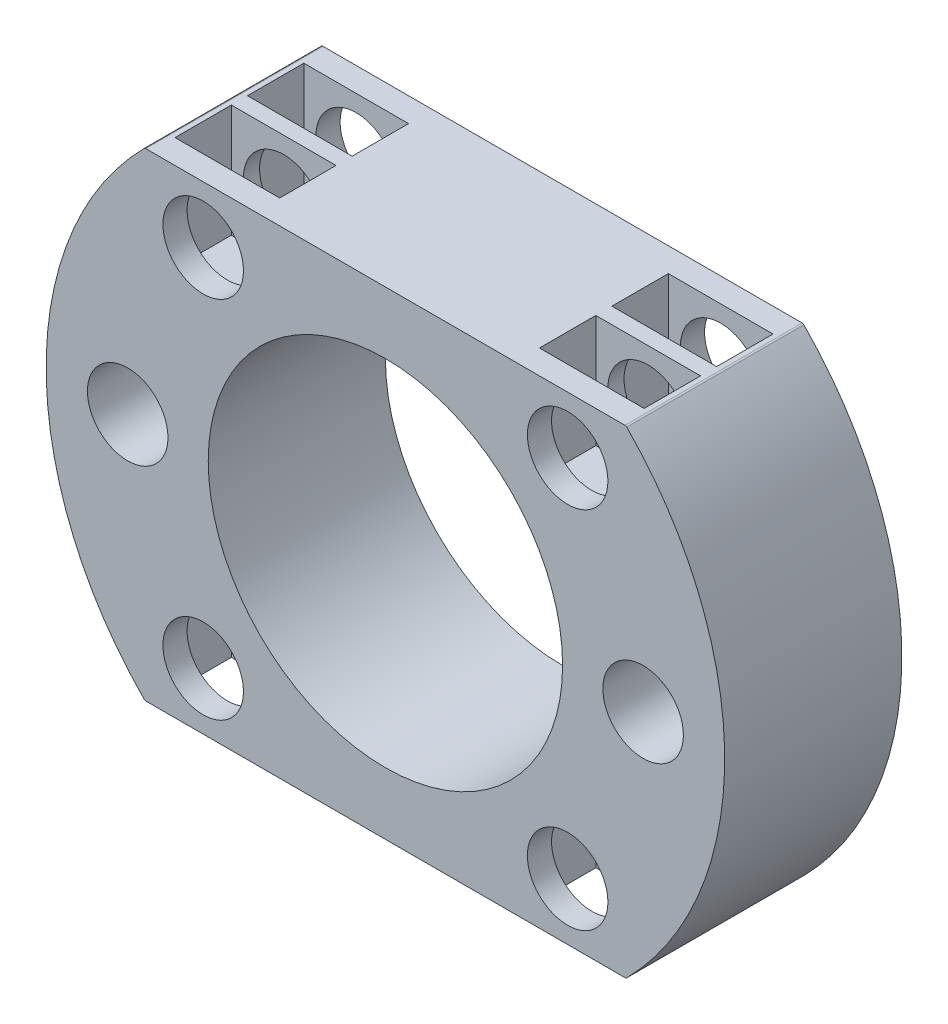
SolidWorks part; units mm, degrees
ref_plane "Plan de face" through (0, 0, 0) normal (0, 0, 1) x (1, 0, 0)
ref_plane "Plan de dessus" through (0, 0, 0) normal (0, 1, 0) x (1, 0, 0)
ref_plane "Plan de droite" through (0, 0, 0) normal (1, 0, 0) x (0, 0, -1)
sketch "Esquisse1" plane through (0, 0, 0) normal (0, 0, 1) x (1, 0, 0)
  line L2 (14.8752, 14.85) -> (-14.8752, 14.85)
  line L3 (-14.8752, -14.85) -> (14.8752, -14.85)
  line L4 (14.8752, 14.85) -> (-14.8752, 14.85)
  line L5 (-14.8752, -14.85) -> (14.8752, -14.85)
  circle A0 centre (-16, 0) radius 2.5 construction
  circle A1 centre (-11.3137, 11.3137) radius 2.5 construction
  circle A2 centre (-11.3137, -11.3137) radius 2.5 construction
  circle A3 centre (11.3137, -11.3137) radius 2.5 construction
  circle A4 centre (16, 0) radius 2.5 construction
  circle A5 centre (11.3137, 11.3137) radius 2.5 construction
  arc A6 (14.8752, -14.85) -> (14.9819, -14.8054) centre (14.8752, -14.7) ccw
  arc A7 (14.9819, -14.8054) -> (14.9819, 14.8054) centre (0, 0) ccw
  arc A8 (14.9819, 14.8054) -> (14.8752, 14.85) centre (14.8752, 14.7) ccw
  arc A9 (-14.8752, 14.85) -> (-14.9819, 14.8054) centre (-14.8752, 14.7) ccw
  arc A10 (-14.9819, 14.8054) -> (-14.9819, -14.8054) centre (0, 0) ccw
  arc A11 (-14.9819, -14.8054) -> (-14.8752, -14.85) centre (-14.8752, -14.7) ccw
  arc A12 (14.8752, -14.85) -> (14.9819, -14.8054) centre (14.8752, -14.7) ccw
  arc A13 (14.9819, -14.8054) -> (14.9819, 14.8054) centre (0, 0) ccw
  arc A14 (14.9819, 14.8054) -> (14.8752, 14.85) centre (14.8752, 14.7) ccw
  arc A15 (-14.8752, 14.85) -> (-14.9819, 14.8054) centre (-14.8752, 14.7) ccw
  arc A16 (-14.9819, 14.8054) -> (-14.9819, -14.8054) centre (0, 0) ccw
  arc A17 (-14.9819, -14.8054) -> (-14.8752, -14.85) centre (-14.8752, -14.7) ccw
  circle A18 centre (-16, 0) radius 2.5
  circle A19 centre (-11.3137, 11.3137) radius 2.5
  circle A20 centre (-11.3137, -11.3137) radius 2.5
  circle A21 centre (11.3137, -11.3137) radius 2.5
  circle A22 centre (16, 0) radius 2.5
  circle A23 centre (11.3137, 11.3137) radius 2.5
  dimension "D1" = 0
extrude "Boss.-Extru.1" add sketch "Esquisse1" along normal up to surface (11 mm away)
sketch "Esquisse2" plane through (0, 14.85, 0) normal (0, 1, 0) x (1, 0, 0)
  line L0 (11.3137, 0.15) -> (11.3137, -10.839) construction
  line L1 (11.3137, 0) -> (11.3137, 0.15) construction
  line L2 (14.8752, 0.15) -> (-14.8752, 0.15) construction
  line L3 (11.3137, -11) -> (11.3137, 0) construction
  line L4 (-14.8752, 0) -> (14.8752, 0) construction
  line L5 (8.0637, -1.5) -> (14.5637, -1.5)
  line L6 (8.0637, -1.5) -> (8.0637, -5)
  line L7 (8.0637, -5) -> (14.5637, -5)
  line L8 (14.5637, -1.5) -> (14.5637, -5)
  line L9 (-11.3137, -11) -> (-11.3137, 0) construction
  line L10 (-8.0637, -1.5) -> (-14.5637, -1.5)
  line L11 (-8.0637, -1.5) -> (-8.0637, -5)
  line L12 (-8.0637, -5) -> (-14.5637, -5)
  line L13 (-14.5637, -1.5) -> (-14.5637, -5)
  line L14 (-14.8752, -5.5) -> (14.8752, -5.5) construction
  line L15 (-14.8752, -11) -> (-14.8752, 0) construction
  line L16 (14.8752, -11) -> (14.8752, 0) construction
  line L17 (14.8752, -11) -> (-14.8752, -11) construction
  line L18 (8.0637, -6) -> (14.5637, -6)
  line L19 (14.5637, -9.5) -> (14.5637, -6)
  line L20 (8.0637, -9.5) -> (14.5637, -9.5)
  line L21 (8.0637, -9.5) -> (8.0637, -6)
  line L22 (-8.0637, -6) -> (-14.5637, -6)
  line L23 (-14.5637, -9.5) -> (-14.5637, -6)
  line L24 (-8.0637, -9.5) -> (-8.0637, -6)
  line L25 (-8.0637, -9.5) -> (-14.5637, -9.5)
  dimension "D1" = 3.25
  dimension "D2" = 3.25
  dimension "D3" = 3.5
  dimension "D4" = 1.5
  dimension "D5" = 3.25
  dimension "D6" = 3.25
  dimension "D7" = 3.5
  dimension "D8" = 1.5
  dimension "D9" = 5.5
extrude "Enlèv. mat.-Extru.1" cut sketch "Esquisse2" against normal blind 7
sketch "Esquisse3" plane through (0, -14.85, 0) normal (0, -1, 0) x (1, 0, 0)
  line L0 (-8.0637, 1.5) -> (-14.5637, 1.5) construction
  line L1 (-8.0637, 5) -> (-8.0637, 1.5) construction
  line L2 (-14.5637, 1.5) -> (-14.5637, 5) construction
  line L3 (-14.5637, 6) -> (-14.5637, 9.5) construction
  line L4 (-8.0637, 9.5) -> (-8.0637, 6) construction
  line L5 (-14.5637, 9.5) -> (-8.0637, 9.5) construction
  line L6 (-8.0637, 6) -> (-14.5637, 6) construction
  line L7 (-14.5637, 5) -> (-8.0637, 5) construction
  line L8 (8.0637, 1.5) -> (8.0637, 5) construction
  line L9 (14.5637, 1.5) -> (8.0637, 1.5) construction
  line L10 (14.5637, 5) -> (14.5637, 1.5) construction
  line L11 (8.0637, 5) -> (14.5637, 5) construction
  line L12 (14.5637, 9.5) -> (14.5637, 6) construction
  line L13 (14.5637, 6) -> (8.0637, 6) construction
  line L14 (8.0637, 6) -> (8.0637, 9.5) construction
  line L15 (8.0637, 9.5) -> (14.5637, 9.5) construction
  line L16 (-8.0637, 1.5) -> (-14.5637, 1.5)
  line L17 (-8.0637, 5) -> (-8.0637, 1.5)
  line L18 (-14.5637, 1.5) -> (-14.5637, 5)
  line L19 (-14.5637, 6) -> (-14.5637, 9.5)
  line L20 (-8.0637, 9.5) -> (-8.0637, 6)
  line L21 (-14.5637, 9.5) -> (-8.0637, 9.5)
  line L22 (-8.0637, 6) -> (-14.5637, 6)
  line L23 (-14.5637, 5) -> (-8.0637, 5)
  line L24 (8.0637, 1.5) -> (8.0637, 5)
  line L25 (14.5637, 1.5) -> (8.0637, 1.5)
  line L26 (14.5637, 5) -> (14.5637, 1.5)
  line L27 (8.0637, 5) -> (14.5637, 5)
  line L28 (14.5637, 9.5) -> (14.5637, 6)
  line L29 (14.5637, 6) -> (8.0637, 6)
  line L30 (8.0637, 6) -> (8.0637, 9.5)
  line L31 (8.0637, 9.5) -> (14.5637, 9.5)
extrude "Enlèv. mat.-Extru.2" cut sketch "Esquisse3" against normal blind 7
sketch "Esquisse4" plane through (0, 0, 11) normal (0, 0, 1) x (1, 0, 0)
  circle A0 centre (0, 0) radius 11 construction
  circle A1 centre (0, 0) radius 11
extrude "Enlèv. mat.-Extru.3" cut sketch "Esquisse4" against normal blind 21
